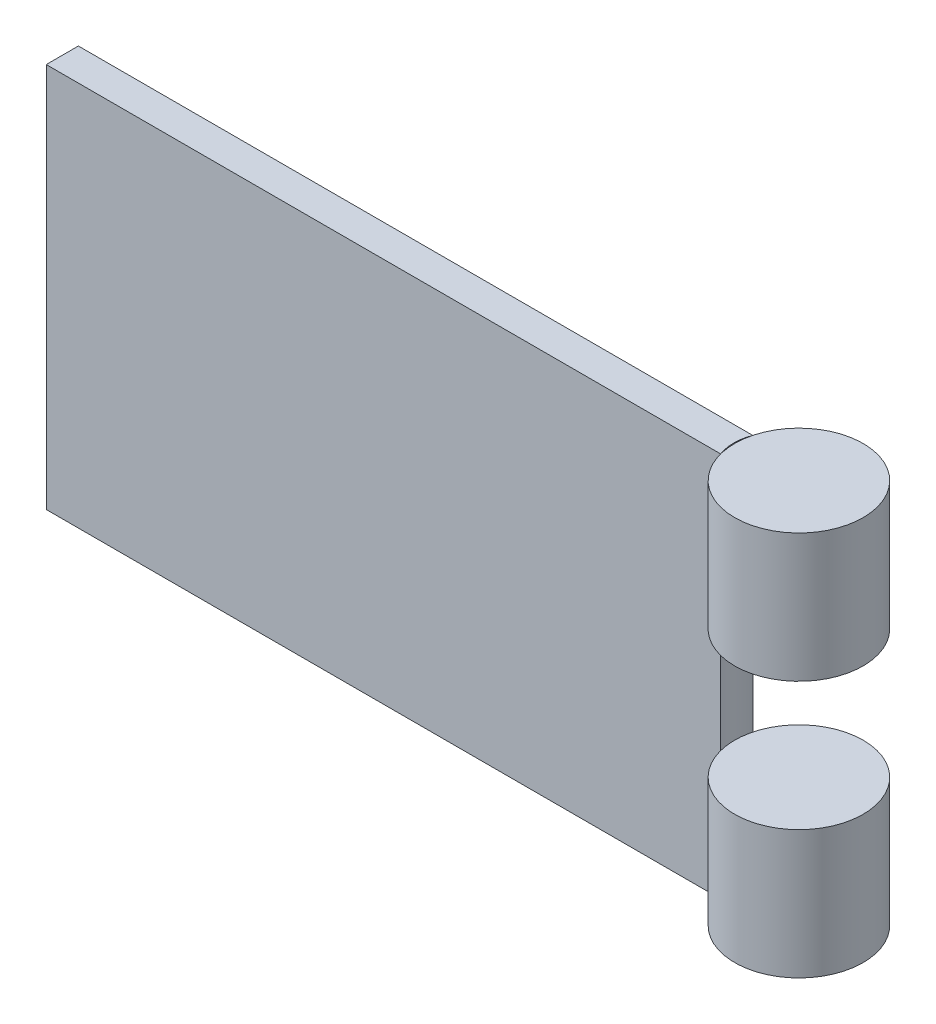
SolidWorks part; units mm, degrees
ref_plane "Front Plane" through (0, 0, 0) normal (0, 0, 1) x (1, 0, 0)
ref_plane "Top Plane" through (0, 0, 0) normal (0, 1, 0) x (1, 0, 0)
ref_plane "Right Plane" through (0, 0, 0) normal (1, 0, 0) x (0, 0, -1)
sketch "Sketch1" plane through (0, 0, 0) normal (0, 0, 1) x (1, 0, 0)
  line L1 (-136.7758, -29.1348) -> (-16.7758, -29.1348)
  line L2 (-136.7758, -29.1348) -> (-136.7758, -89.1348)
  line L3 (-136.7758, -89.1348) -> (-16.7758, -89.1348)
  line L4 (-16.7758, -29.1348) -> (-16.7758, -89.1348)
  dimension "D1" = 120
  dimension "D2" = 60
extrude "Boss-Extrude4" add sketch "Sketch1" along normal blind 5
sketch "Sketch6" plane through (0, -29.1348, 0) normal (0, 1, 0) x (1, 0, 0)
  arc A0 (-16.7758, 0) -> (-16.7758, -5) centre (-10.2374, -2.5) ccw
  dimension "D1" = 7
extrude "Cut-Extrude3" cut sketch "Sketch6" against normal blind 60 and the other way through all
sketch "Sketch18" plane through (0, -29.1348, 0) normal (0, 1, 0) x (1, 0, 0)
  circle A0 centre (-7.0933, -2.5) radius 10
  dimension "D1" = 10
extrude "Boss-Extrude9" add sketch "Sketch18" against normal blind 20 separate body
sketch "Sketch19" plane through (0, -89.1348, 0) normal (0, -1, 0) x (1, 0, 0)
  circle A0 centre (-7.0933, 2.5) radius 10
extrude "Boss-Extrude10" add sketch "Sketch19" against normal blind 20 separate body
sketch "Sketch20" plane through (0, 0, 0) normal (0, 0, -1) x (-1, 0, 0)
  line L0 (136.7758, -89.1348) -> (16.7758, -89.1348) construction
  line L1 (136.7758, -29.1348) -> (121.7758, -29.1348)
  line L2 (136.7758, -29.1348) -> (136.7758, -89.1348)
  line L3 (136.7758, -89.1348) -> (121.7758, -89.1348)
  line L4 (121.7758, -29.1348) -> (121.7758, -89.1348)
  dimension "D1" = 15
extrude "Cut-Extrude4" cut sketch "Sketch20" against normal blind 10
